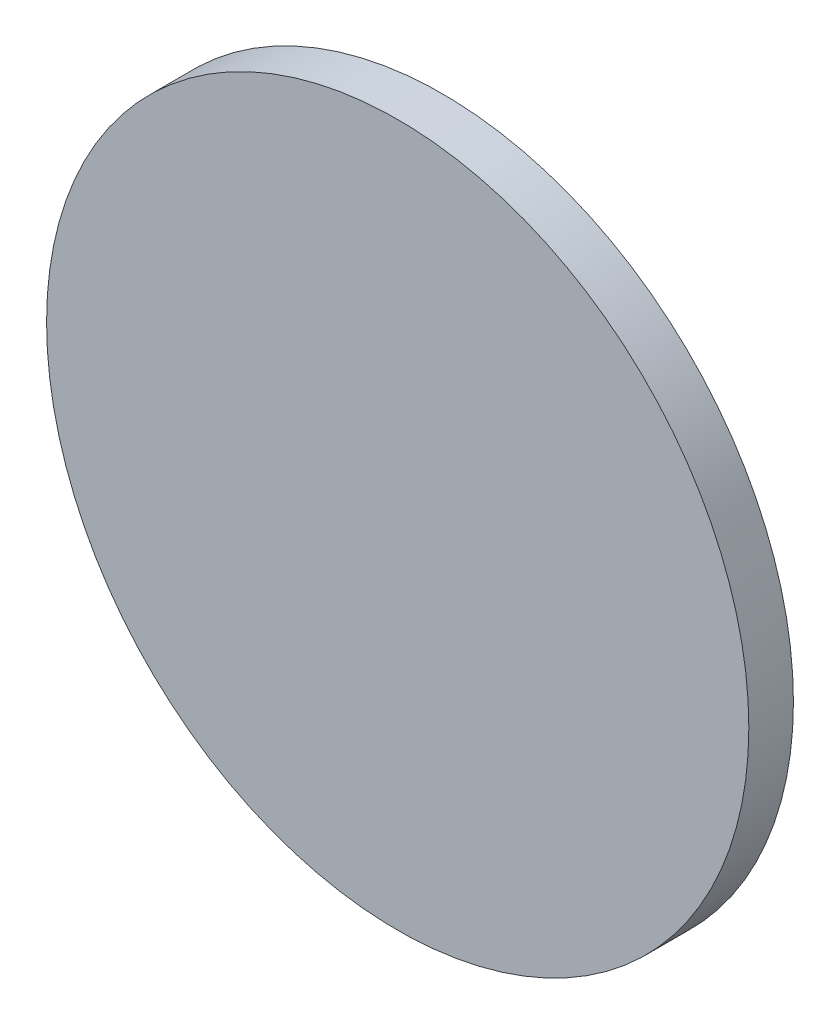
SolidWorks part; units mm, degrees
material "Custom Plastic"
ref_plane "X-Y Datum" through (0, 0, 0) normal (0, 0, 1) x (1, 0, 0)
ref_plane "X-Z Datum" through (0, 0, 0) normal (0, 1, 0) x (1, 0, 0)
ref_plane "Y-Z Datum" through (0, 0, 0) normal (1, 0, 0) x (0, 0, -1)
sketch "Sketch1" plane through (0, 0, 0) normal (0, 0, 1) x (1, 0, 0)
  circle A0 centre (0, 0) radius 25
  dimension "D1" = 50
extrude "Boss-Extrude1" add sketch "Sketch1" along normal blind 3.175
